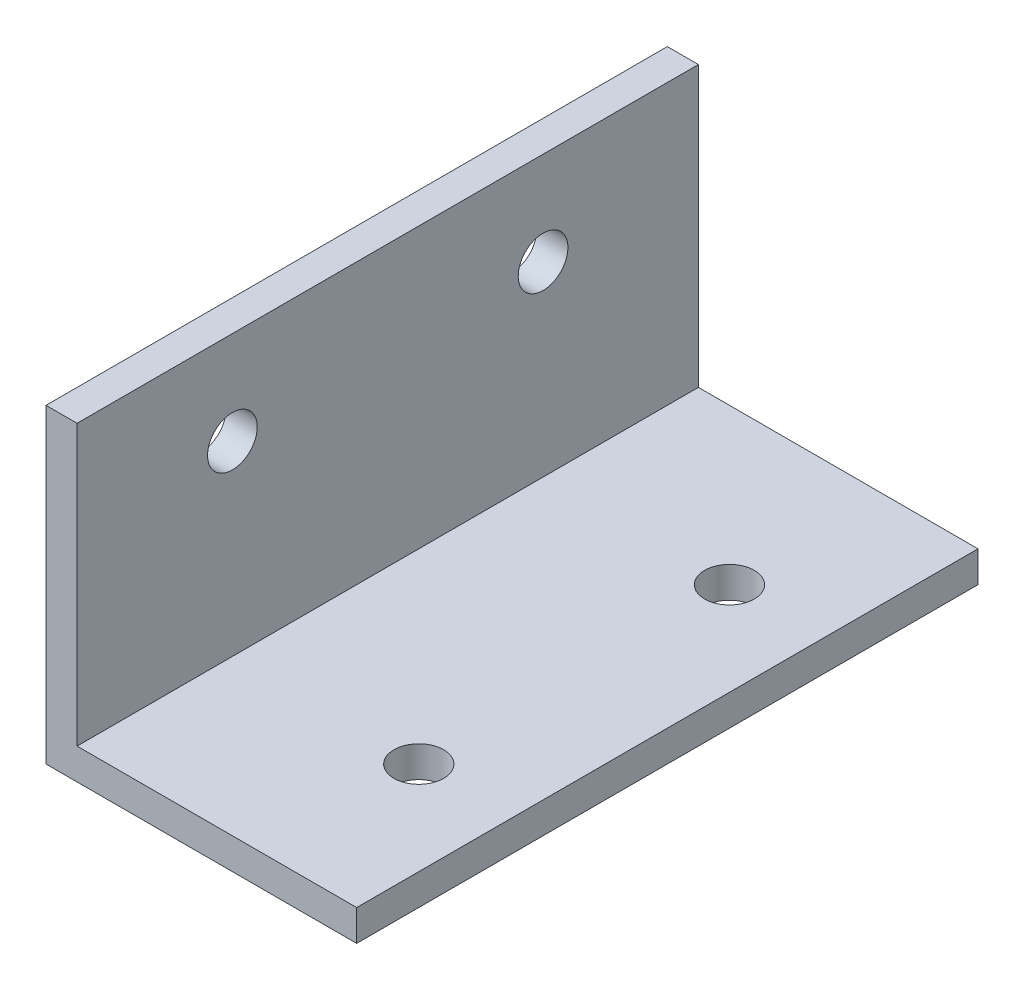
SolidWorks part; units mm, degrees
ref_plane "Front Plane" through (0, 0, 0) normal (0, 0, 1) x (1, 0, 0)
ref_plane "Top Plane" through (0, 0, 0) normal (0, 1, 0) x (1, 0, 0)
ref_plane "Right Plane" through (0, 0, 0) normal (1, 0, 0) x (0, 0, -1)
sketch "Sketch1" plane through (0, 0, 0) normal (0, 0, 1) x (1, 0, 0)
  line L0 (0, 50) -> (5, 50)
  line L1 (5, 50) -> (5, 5)
  line L2 (5, 5) -> (50, 5)
  line L3 (50, 5) -> (50, 0)
  line L4 (50, 0) -> (0, 0)
  line L5 (0, 0) -> (0, 50)
  dimension "D1" = 5
  dimension "D2" = 50
extrude "Boss-Extrude1" add sketch "Sketch1" along normal mid plane 100
sketch "Sketch2" plane through (5, 0, 0) normal (1, 0, 0) x (0, 0, -1)
  line L0 (-50, 50) -> (50, 50) construction
  circle A0 centre (-25, 35) radius 4
  circle A1 centre (25, 35) radius 4
  point P4 (0, 0)
  point P7 (0, 0)
  point P8 (-31.4758, 35)
  point P9 (-83.4125, 34.4145)
  dimension "D1" = 8
  dimension "D2" = 15
  dimension "D3" = 50
  dimension "D4" = 25
sketch "Sketch3" plane through (0, 5, 0) normal (0, 1, 0) x (1, 0, 0)
  line L0 (50, -50) -> (50, 50) construction
  circle A0 centre (35, 25) radius 4
  circle A1 centre (35, -25) radius 4
  point P4 (0, 0)
  dimension "D2" = 8
  dimension "D1" = 50
  dimension "D3" = 25
  dimension "D4" = 15
extrude "Cut-Extrude1" cut sketch "Sketch3" against normal through all
extrude "Cut-Extrude2" cut sketch "Sketch2" against normal blind 200
